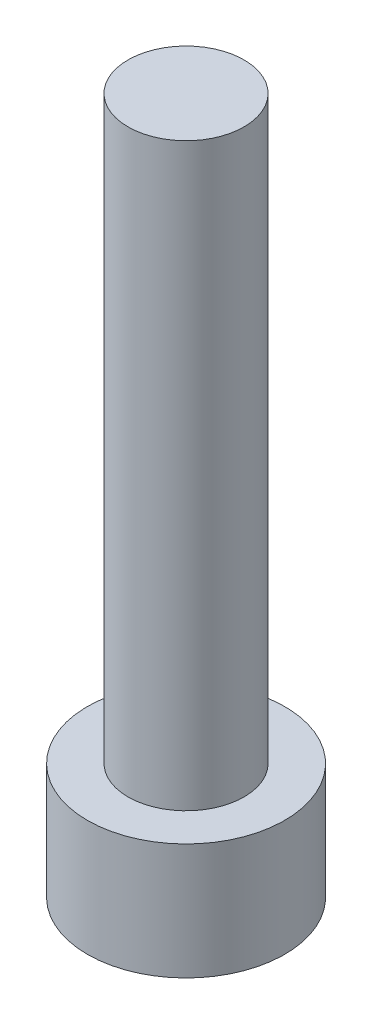
SolidWorks part; units mm, degrees
material "不锈钢 (铁素体)"
ref_plane "前视基准面" through (0, 0, 0) normal (0, 0, 1) x (1, 0, 0)
ref_plane "上视基准面" through (0, 0, 0) normal (0, 1, 0) x (1, 0, 0)
ref_plane "右视基准面" through (0, 0, 0) normal (1, 0, 0) x (0, 0, -1)
sketch "草图1" plane through (0, 0, 0) normal (0, 1, 0) x (1, 0, 0)
  circle A0 centre (0, 0) radius 5.1
  dimension "D1" = 10.2
extrude "凸台-拉伸1" add sketch "草图1" along normal blind 6
sketch "草图2" plane through (0, 6, 0) normal (0, 1, 0) x (1, 0, 0)
  circle A0 centre (0, 0) radius 3
  dimension "D1" = 6
extrude "凸台-拉伸2" add sketch "草图2" along normal blind 30
